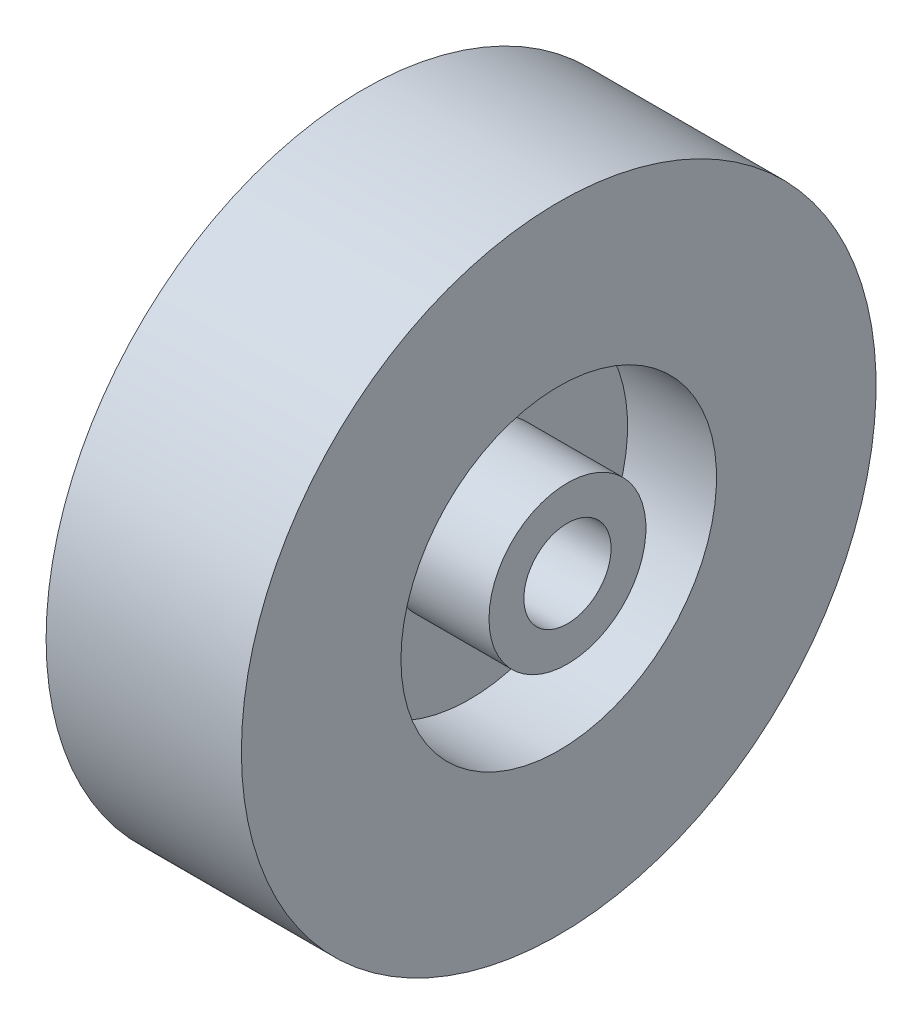
SolidWorks part; units mm, degrees
ref_plane "Front Plane" through (0, 0, 0) normal (0, 0, 1) x (1, 0, 0)
ref_plane "Top Plane" through (0, 0, 0) normal (0, 1, 0) x (1, 0, 0)
ref_plane "Right Plane" through (0, 0, 0) normal (1, 0, 0) x (0, 0, -1)
sketch "Sketch1" plane through (0, 0, 0) normal (0, 0, 1) x (1, 0, 0)
  line L0 (0, 36.4) -> (0, -12.6209) construction
  line L1 (-11.2, 18.1) -> (-1, 18.1)
  line L2 (11.2, 36.4) -> (-11.2, 36.4)
  line L3 (-11.2, 36.4) -> (-11.2, 18.1)
  line L4 (-13.5809, 0) -> (0, 0) construction
  line L5 (-1, 18.1) -> (-1, 9)
  line L6 (-1, 9) -> (-12.2, 9)
  line L7 (-12.2, 9) -> (-12.2, 0)
  line L8 (0, 0) -> (22.7343, 0) construction
  line L9 (12.2, 9) -> (12.2, 0)
  line L10 (1, 9) -> (12.2, 9)
  line L11 (1, 18.1) -> (1, 9)
  line L12 (11.2, 36.4) -> (11.2, 18.1)
  line L13 (11.2, 18.1) -> (1, 18.1)
  line L14 (-12.2, 0) -> (12.2, 0)
  dimension "D1" = 11.2
  dimension "D2" = 18.3
  dimension "D3" = 10.2
  dimension "D4" = 9
  dimension "D5" = 9.1
  dimension "D6" = 11.2
revolve "Revolve1" add sketch "Sketch1" angle 360 about L8
sketch "Sketch2" plane through (12.2, 0, 0) normal (1, 0, 0) x (0, 0, -1)
  circle A0 centre (0, 0) radius 5
  dimension "D1" = 10
extrude "Cut-Extrude1" cut sketch "Sketch2" against normal blind 15
